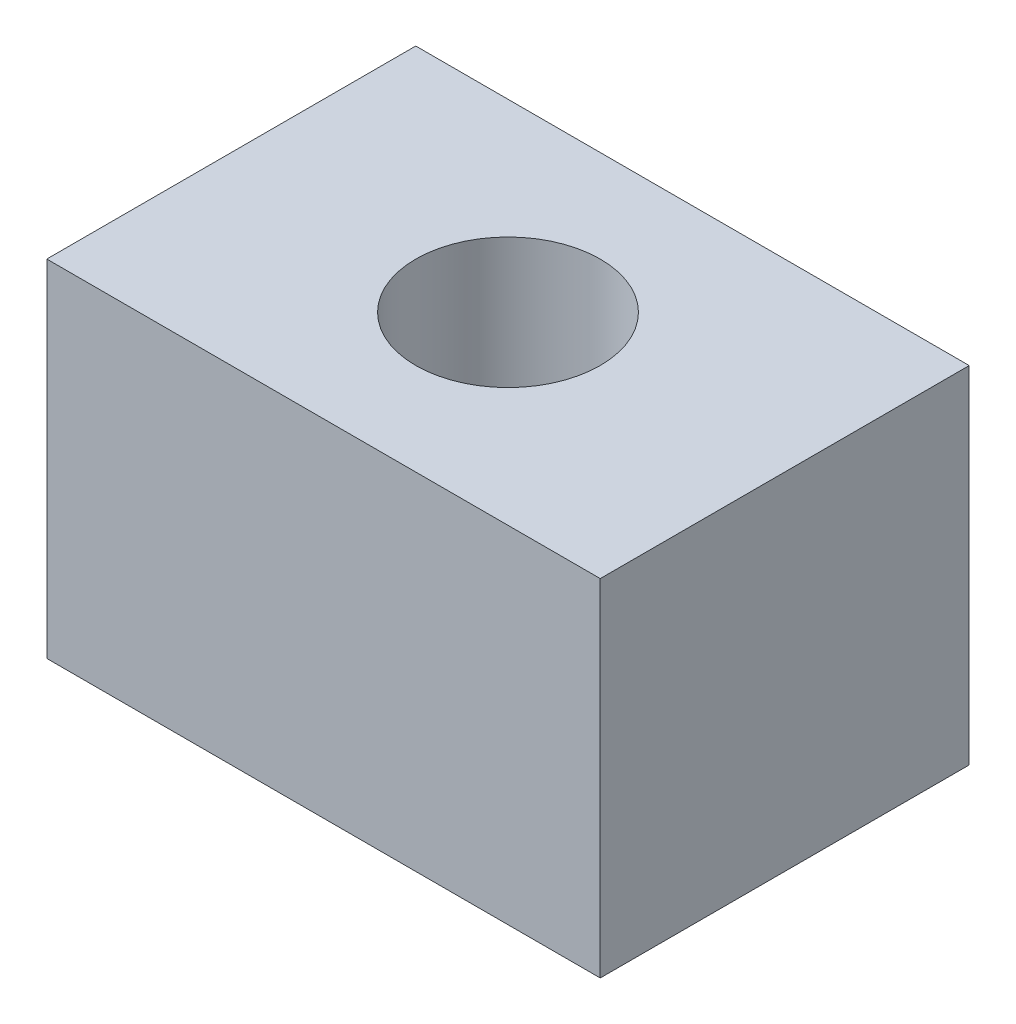
SolidWorks part; units mm, degrees
ref_plane "Front Plane" through (0, 0, 0) normal (0, 0, 1) x (1, 0, 0)
ref_plane "Top Plane" through (0, 0, 0) normal (0, 1, 0) x (1, 0, 0)
ref_plane "Right Plane" through (0, 0, 0) normal (1, 0, 0) x (0, 0, -1)
sketch "Sketch1" plane through (0, 0, 0) normal (0, 1, 0) x (1, 0, 0)
  line L1 (0, 0) -> (15.24, 0)
  line L2 (0, 0) -> (0, 10.16)
  line L3 (0, 10.16) -> (15.24, 10.16)
  line L4 (15.24, 0) -> (15.24, 10.16)
  dimension "D1" = 15.24
  dimension "D2" = 10.16
extrude "Boss-Extrude1" add sketch "Sketch1" along normal blind 9.525
sketch "Sketch2" plane through (0, 9.525, 0) normal (0, 1, 0) x (1, 0, 0)
  line L0 (0, 10.16) -> (15.24, 0) construction
  line L1 (15.24, 0) -> (15.24, 10.16) construction
  line L2 (15.24, 10.16) -> (0, 0) construction
  circle A0 centre (7.62, 5.08) radius 2.54
  dimension "D1" = 5.08
extrude "Cut-Extrude1" cut sketch "Sketch2" against normal through all
